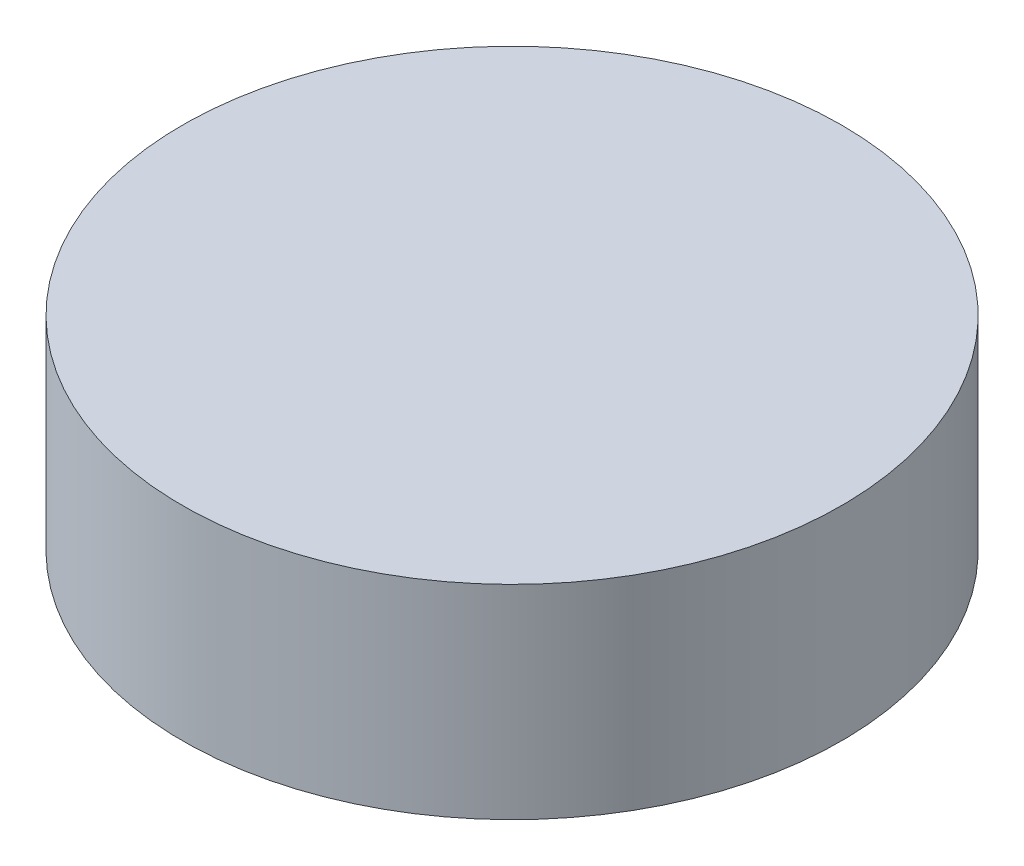
SolidWorks part; units mm, degrees
ref_plane "前视基准面" through (0, 0, 0) normal (0, 0, 1) x (1, 0, 0)
ref_plane "上视基准面" through (0, 0, 0) normal (0, 1, 0) x (1, 0, 0)
ref_plane "右视基准面" through (0, 0, 0) normal (1, 0, 0) x (0, 0, -1)
other "Configuration Table"
sketch "Sketch2" plane through (0, 0, 0) normal (0, 1, 0) x (1, 0, 0)
  circle A0 centre (0, 0) radius 61.6204
  dimension "D1" = 123.2408
extrude "Boss-Extrude1" add sketch "Sketch2" along normal mid plane 38.1
